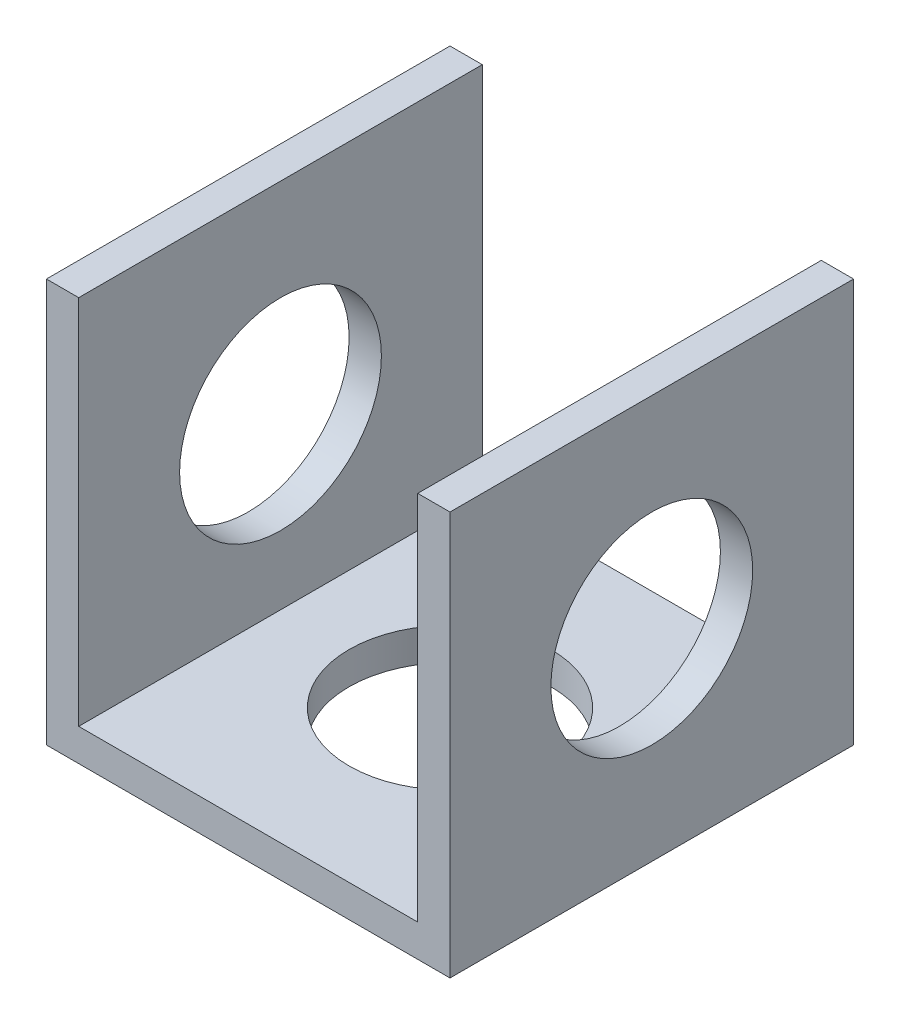
SolidWorks part; units mm, degrees
ref_plane "Front Plane" through (0, 0, 0) normal (0, 0, 1) x (1, 0, 0)
ref_plane "Top Plane" through (0, 0, 0) normal (0, 1, 0) x (1, 0, 0)
ref_plane "Right Plane" through (0, 0, 0) normal (1, 0, 0) x (0, 0, -1)
sketch "Sketch1" plane through (0, 0, 0) normal (1, 0, 0) x (0, 0, -1)
  line L1 (0, 0) -> (6.35, 0)
  line L2 (0, 0) -> (0, 6.35)
  line L3 (0, 6.35) -> (6.35, 6.35)
  line L4 (6.35, 0) -> (6.35, 6.35)
  dimension "D1" = 6.35
  dimension "D2" = 6.35
extrude "Boss-Extrude1" add sketch "Sketch1" along normal blind 6.35
hole_wizard "1/8 (0.125) Diameter Hole1" positions "Sketch3" profile "Sketch2" hole size "1/8" standard "ANSI Inch"
sketch "Sketch3" plane through (6.35, 0, 0) normal (1, 0, 0) x (0, 0, -1)
  line L0 (6.35, 0) -> (6.35, 6.35) construction
  line L1 (6.35, 6.35) -> (0, 6.35) construction
  point P0 (3.175, 3.175)
  point P3 (6.35, 3.175)
  point P6 (3.175, 6.35)
  dimension "D1" = 0
  dimension "D2" = 0
sketch "Sketch2" plane through (6.35, 3.175, -3.175) normal (0, 1, 0) x (0, 0, -1)
  line L0 (0, 0) -> (0, 71.0579)
  line L1 (0, 71.0579) -> (1.5875, 70.104)
  line L2 (1.5875, 70.104) -> (1.5875, 0)
  line L5 (1.5875, 0) -> (0, 0)
  line L10 (0, 71.0579) -> (-1.5875, 70.104) construction
  line L11 (0, -6.35) -> (0, 107.95) construction
  dimension "Hole Dia." = 3.175
  dimension "Hole Depth" = 70.104
  dimension "Drill Angle" = 118
sketch "Sketch4" plane through (0, 0, -6.35) normal (0, 0, -1) x (-1, 0, 0)
  line L0 (-6.35, 6.35) -> (0, 6.35) construction
  line L1 (-5.842, 6.35) -> (-0.508, 6.35)
  line L2 (-5.842, 6.35) -> (-5.842, 0.508)
  line L3 (-5.842, 0.508) -> (-0.508, 0.508)
  line L4 (-0.508, 6.35) -> (-0.508, 0.508)
  line L5 (0, 0) -> (0, 6.35) construction
  line L6 (-6.35, 0) -> (-6.35, 6.35) construction
  line L7 (-6.35, 0) -> (0, 0) construction
  dimension "D1" = 0.508
  dimension "D2" = 0.508
  dimension "D3" = 0.508
extrude "Cut-Extrude1" cut sketch "Sketch4" against normal through all
hole_wizard "1/8 (0.125) Diameter Hole2" positions "Sketch6" profile "Sketch5" hole size "1/8" standard "ANSI Inch"
sketch "Sketch6" plane through (0, 0, 0) normal (0, -1, 0) x (-1, 0, 0)
  line L0 (-5.842, 6.35) -> (-0.508, 6.35) construction
  line L1 (0, 0) -> (0, 6.35) construction
  point P0 (-3.175, 3.175)
  point P3 (-3.175, 6.35)
  point P8 (0, 3.175)
  dimension "D1" = 0
  dimension "D2" = 0
sketch "Sketch5" plane through (3.175, 0, -3.175) normal (1, 0, 0) x (0, 0, -1)
  line L0 (0, 0) -> (0, 71.0579)
  line L1 (0, 71.0579) -> (1.5875, 70.104)
  line L2 (1.5875, 70.104) -> (1.5875, 0)
  line L5 (1.5875, 0) -> (0, 0)
  line L10 (0, 71.0579) -> (-1.5875, 70.104) construction
  line L11 (0, -6.35) -> (0, 107.95) construction
  dimension "Hole Dia." = 3.175
  dimension "Hole Depth" = 70.104
  dimension "Drill Angle" = 118
